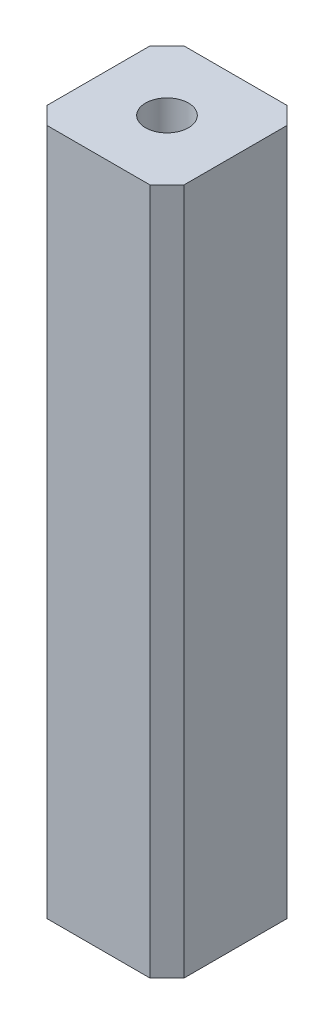
SolidWorks part; units mm, degrees
ref_plane "Спереди" through (0, 0, 0) normal (0, 0, 1) x (1, 0, 0)
ref_plane "Сверху" through (0, 0, 0) normal (0, 1, 0) x (1, 0, 0)
ref_plane "Справа" through (0, 0, 0) normal (1, 0, 0) x (0, 0, -1)
sketch "Эскиз1" plane through (0, 0, 0) normal (0, 1, 0) x (1, 0, 0)
  line L1 (-4, -4) -> (4, -4)
  line L2 (-4, -4) -> (-4, 4)
  line L3 (-4, 4) -> (4, 4)
  line L4 (4, -4) -> (4, 4)
  line L5 (-4, -4) -> (4, 4) construction
  line L6 (-4, 4) -> (4, -4) construction
  circle A1 centre (0, 0) radius 1.25
  dimension "D1" = 2.5
  dimension "D2" = 8
extrude "тело" add sketch "Эскиз1" along normal blind 40
chamfer "Фаска1" distance 1 angle 45 4 edges at (4, 20, -4) (-4, 20, -4) (-4, 20, 4) (4, 20, 4)
